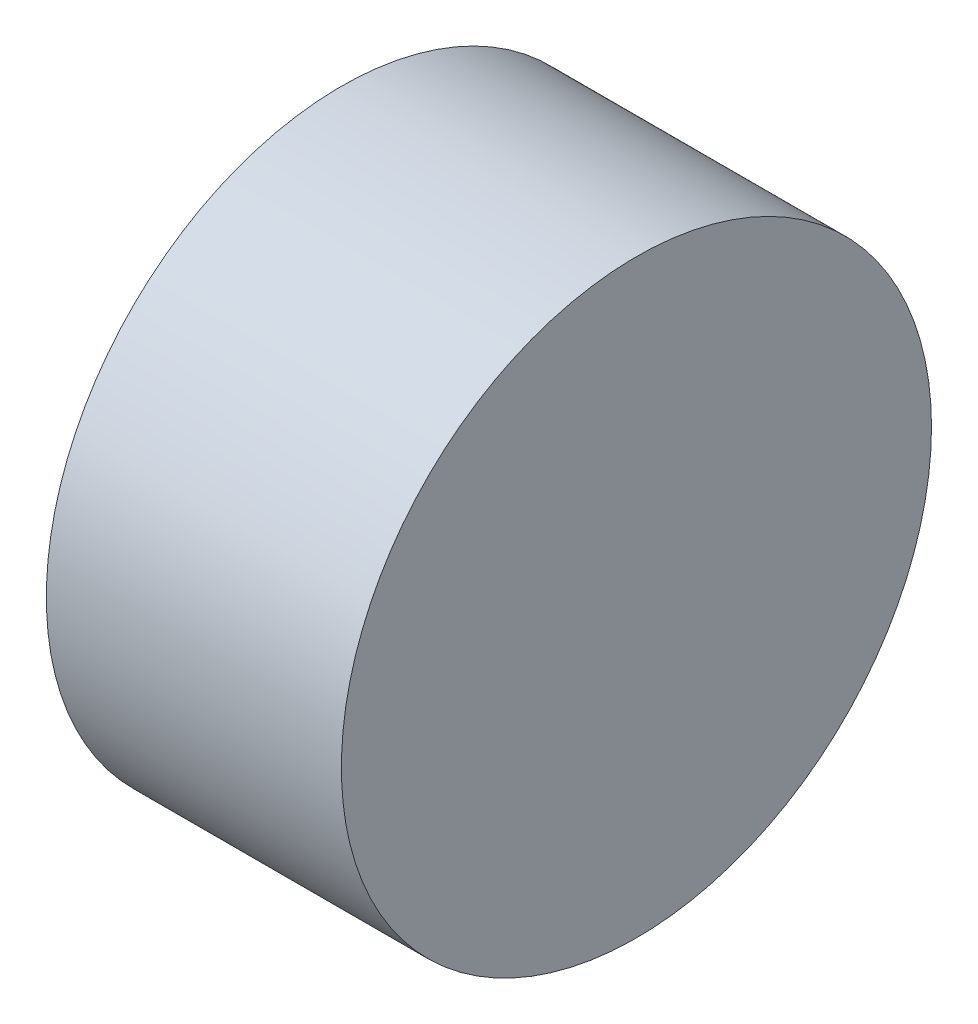
SolidWorks part; units mm, degrees
ref_plane "Front" through (0, 0, 0) normal (0, 0, 1) x (1, 0, 0)
ref_plane "Top" through (0, 0, 0) normal (0, 1, 0) x (1, 0, 0)
ref_plane "Right" through (0, 0, 0) normal (1, 0, 0) x (0, 0, -1)
sketch "Sketch1" plane through (0, 0, 0) normal (1, 0, 0) x (0, 0, -1)
  circle A0 centre (0, 0) radius 50.8
  dimension "D1" = 101.6
extrude "Boss-Extrude1" add sketch "Sketch1" along normal mid plane 50.8
